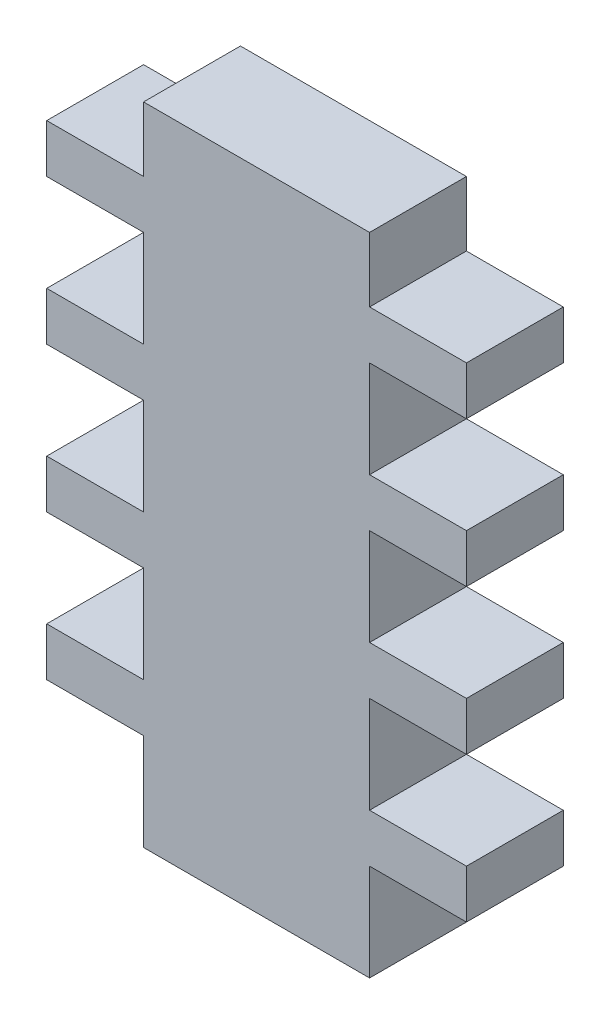
SolidWorks part; units mm, degrees
ref_plane "Plan de face" through (0, 0, 0) normal (0, 0, 1) x (1, 0, 0)
ref_plane "Plan de dessus" through (0, 0, 0) normal (0, 1, 0) x (1, 0, 0)
ref_plane "Plan de droite" through (0, 0, 0) normal (1, 0, 0) x (0, 0, -1)
sketch "Sketch1" plane through (0, 0, 0) normal (0, 0, 1) x (1, 0, 0)
  line L1 (-6.5, -10) -> (6.5, -10)
  line L2 (-6.5, -10) -> (-6.5, 10)
  line L3 (-6.5, 10) -> (6.5, 10)
  line L4 (6.5, -10) -> (6.5, 10)
  line L5 (-6.5, -10) -> (6.5, 10) construction
  line L6 (-6.5, 10) -> (6.5, -10) construction
  point P0 (0, 0)
  dimension "D1" = 13
  dimension "D2" = 20
extrude "Boss-Extrude1" add sketch "Sketch1" along normal blind 3
sketch "Sketch2" plane through (0, 0, 3) normal (0, 0, 1) x (1, 0, 0)
  line L0 (-6.5, 10) -> (-6.5, -10) construction
  line L1 (-6.5, 8) -> (-3.5, 8)
  line L2 (-6.5, 8) -> (-6.5, 10)
  line L3 (-6.5, 10) -> (-3.5, 10)
  line L4 (-3.5, 8) -> (-3.5, 10)
  line L5 (6.5, 10) -> (-6.5, 10) construction
  line L7 (-6.5, 6.5) -> (-3.5, 6.5)
  line L8 (-6.5, 6.5) -> (-6.5, 3.5)
  line L9 (-6.5, 3.5) -> (-3.5, 3.5)
  line L10 (-3.5, 6.5) -> (-3.5, 3.5)
  line L11 (-6.5, 2) -> (-3.5, 2)
  line L12 (-6.5, 2) -> (-6.5, -1)
  line L13 (-6.5, -1) -> (-3.5, -1)
  line L14 (-3.5, 2) -> (-3.5, -1)
  line L15 (-6.5, -2.5) -> (-3.5, -2.5)
  line L16 (-6.5, -2.5) -> (-6.5, -5.5)
  line L17 (-6.5, -5.5) -> (-3.5, -5.5)
  line L18 (-3.5, -2.5) -> (-3.5, -5.5)
  line L19 (-6.5, -7) -> (-3.5, -7)
  line L20 (-6.5, -7) -> (-6.5, -10)
  line L21 (-6.5, -10) -> (-3.5, -10)
  line L22 (-3.5, -7) -> (-3.5, -10)
  dimension "D1" = 2
  dimension "D2" = 3
  dimension "D3" = 1.5
  dimension "D4" = 3
  dimension "D5" = 3
  dimension "D6" = 3
  dimension "D7" = 3
  dimension "D8" = 1.5
  dimension "D9" = 3
  dimension "D10" = 1.5
  dimension "D11" = 3
  dimension "D12" = 1.5
extrude "Cut-Extrude1" cut sketch "Sketch2" against normal blind 3
sketch "Sketch3" plane through (0, 0, 3) normal (0, 0, 1) x (1, 0, 0)
  line L0 (6.5, 10) -> (-3.5, 10) construction
  line L1 (3.5, 10) -> (6.5, 10)
  line L2 (3.5, 10) -> (3.5, 8)
  line L3 (3.5, 8) -> (6.5, 8)
  line L4 (6.5, 10) -> (6.5, 8)
  line L5 (6.5, -10) -> (6.5, 10) construction
  line L6 (-3.5, -10) -> (6.5, -10) construction
  line L7 (6.5, 6.5) -> (3.5, 6.5)
  line L8 (6.5, 6.5) -> (6.5, 3.5)
  line L9 (6.5, 3.5) -> (3.5, 3.5)
  line L10 (3.5, 6.5) -> (3.5, 3.5)
  line L11 (6.5, 2) -> (3.5, 2)
  line L12 (6.5, 2) -> (6.5, -1)
  line L13 (6.5, -1) -> (3.5, -1)
  line L14 (3.5, 2) -> (3.5, -1)
  line L15 (6.5, -2.5) -> (3.5, -2.5)
  line L16 (6.5, -2.5) -> (6.5, -5.5)
  line L17 (6.5, -5.5) -> (3.5, -5.5)
  line L18 (3.5, -2.5) -> (3.5, -5.5)
  line L19 (6.5, -7) -> (3.5, -7)
  line L20 (6.5, -7) -> (6.5, -10)
  line L21 (6.5, -10) -> (3.5, -10)
  line L22 (3.5, -7) -> (3.5, -10)
  point P16 (5, 2)
  dimension "D1" = 2
  dimension "D2" = 3
  dimension "D3" = 1.5
  dimension "D4" = 3
  dimension "D5" = 3
  dimension "D6" = 1.5
  dimension "D7" = 3
  dimension "D8" = 3
  dimension "D9" = 3
  dimension "D10" = 1.5
  dimension "D11" = 3
extrude "Cut-Extrude2" cut sketch "Sketch3" against normal blind 3
